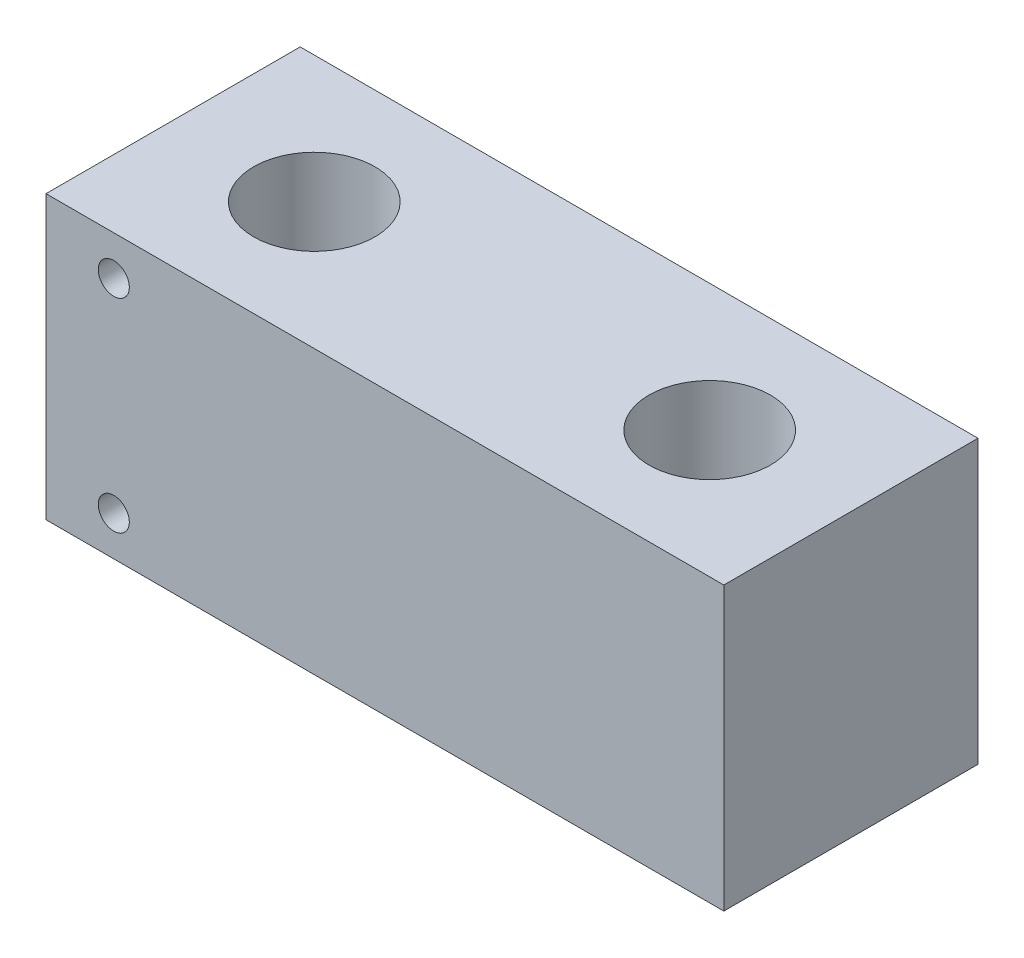
SolidWorks part; units mm, degrees
material "普通碳钢"
ref_plane "前视基准面" through (0, 0, 0) normal (0, 0, 1) x (1, 0, 0)
ref_plane "上视基准面" through (0, 0, 0) normal (0, 1, 0) x (1, 0, 0)
ref_plane "右视基准面" through (0, 0, 0) normal (1, 0, 0) x (0, 0, -1)
sketch "草图1" plane through (0, 0, 0) normal (0, 1, 0) x (1, 0, 0)
  line L0 (0, 22.5) -> (0, -22.5) construction
  line L1 (-60, 22.5) -> (60, 22.5)
  line L2 (-60, 22.5) -> (-60, -22.5)
  line L3 (-60, -22.5) -> (60, -22.5)
  line L4 (60, 22.5) -> (60, -22.5)
  line L5 (-60, 22.5) -> (60, -22.5) construction
  line L6 (-60, -22.5) -> (60, 22.5) construction
  line L7 (-60, 0) -> (60, 0) construction
  circle A0 centre (-35, 0) radius 10.75
  circle A1 centre (35, 0) radius 10.75
  point P0 (0, 0)
  dimension "D4" = 21.5
  dimension "D1" = 120
  dimension "D2" = 45
  dimension "D3" = 35
extrude "凸台-拉伸1" add sketch "草图1" along normal blind 50
hole_wizard "M6 螺纹孔1" positions "3D草图2" profile "草图9" tap size "M6" standard "GB"
sketch3d "3D草图2"
  line L0 (-48, 43, 22.5) -> (-48, 7, 22.5) construction
  line L1 (0, 50, 22.5) -> (0, 0, 22.5) construction
  line L2 (-60, 50, 22.5) -> (60, 50, 22.5) construction
  line L3 (-60, 0, 22.5) -> (60, 0, 22.5) construction
  line L4 (-48, 25, 22.5) -> (0, 25, 22.5) construction
  point P0 (-48, 43, 22.5)
  point P2 (-48, 7, 22.5)
  dimension "D1" = 48
  dimension "D2" = 36
sketch "草图9" plane through (-48, 43, 22.5) normal (1, 0, 0) x (0, -1, 0)
  line L0 (0, 0) -> (0, 16.6524)
  line L1 (0, 16.6524) -> (2.75, 15)
  line L2 (2.75, 15) -> (2.75, 0)
  line L5 (2.75, 0) -> (0, 0)
  line L10 (0, 16.6524) -> (-2.75, 15) construction
  line L11 (0, -6.35) -> (0, 107.95) construction
  dimension "螺纹孔钻头直径" = 5.5
  dimension "螺纹孔钻头深度" = 15
  dimension "导头角度" = 118
cosmetic thread "孔螺蚊线5" parameters "D1"=12, "D2"=6
cosmetic thread "孔螺蚊线6" parameters "D1"=12, "D2"=6
